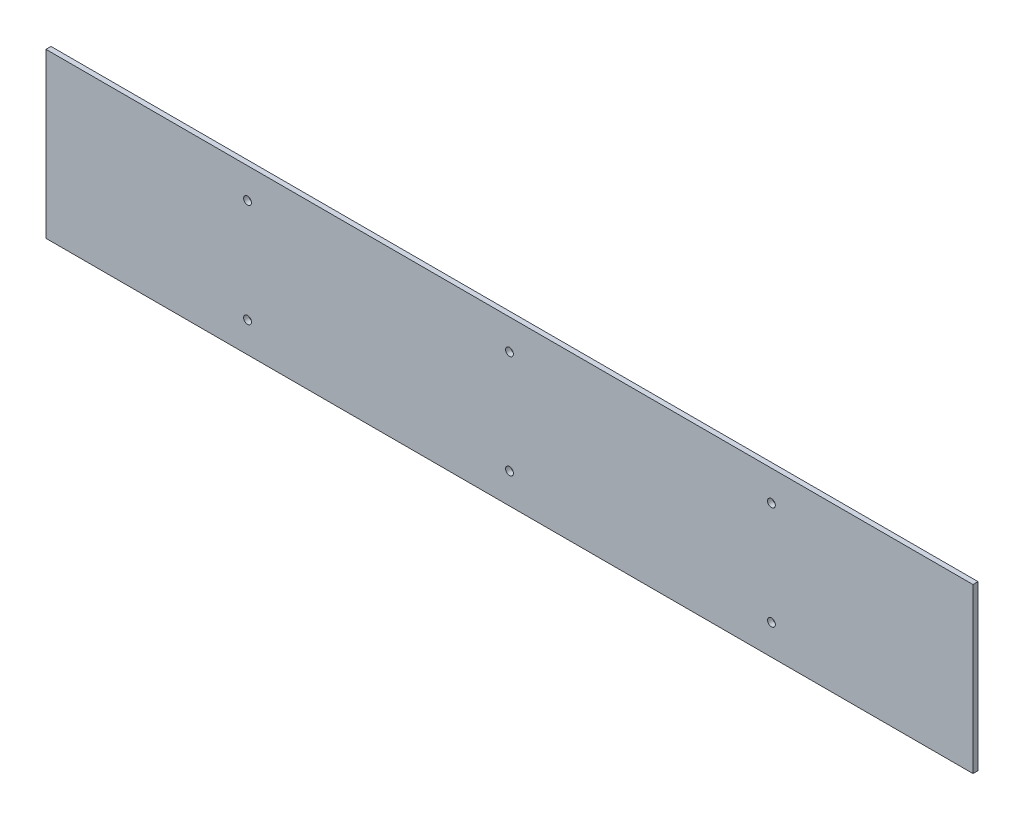
SolidWorks part; units mm, degrees
material "ABS PC"
ref_plane "Front Plane" through (0, 0, 0) normal (0, 0, 1) x (1, 0, 0)
ref_plane "Top Plane" through (0, 0, 0) normal (0, 1, 0) x (1, 0, 0)
ref_plane "Right Plane" through (0, 0, 0) normal (1, 0, 0) x (0, 0, -1)
sketch "Sketch2" plane through (0, 0, 0) normal (0, 0, 1) x (1, 0, 0)
  line L1 (0, 0) -> (584.2, 0)
  line L2 (0, 0) -> (0, 103.1875)
  line L3 (0, 103.1875) -> (584.2, 103.1875)
  line L4 (584.2, 0) -> (584.2, 103.1875)
  dimension "D1" = 103.1875
  dimension "D2" = 584.2
extrude "Boss-Extrude1" add sketch "Sketch2" along normal blind 3.175
hole_wizard "#10 (0.1935) Diameter Hole1" positions "Sketch3" profile "Sketch4" hole size "#10" standard "ANSI Inch" end condition through all
sketch "Sketch3" plane through (0, 0, 3.175) normal (0, 0, 1) x (1, 0, 0)
  line L2 (292.1, 103.1875) -> (292.1, 0) construction
  line L3 (584.2, 103.1875) -> (0, 103.1875) construction
  line L4 (0, 0) -> (584.2, 0) construction
  line L5 (127, 84.1375) -> (501.65, 84.1375) construction
  point P0 (127, 84.1375)
  point P2 (292.1, 84.1375)
  point P4 (457.2, 84.1375)
  dimension "D1" = 0
  dimension "D2" = 19.05
  dimension "D3" = 19.05
  dimension "D4" = 165.1
  dimension "D5" = 165.1
  dimension "D6" = 19.05
sketch "Sketch4" plane through (127, 84.1375, 3.175) normal (1, 0, 0) x (0, -1, 0)
  line L0 (0, 0) -> (0, 3.175)
  line L1 (0, 3.175) -> (2.4574, 3.175)
  line L2 (2.4574, 3.175) -> (2.4574, 0)
  line L5 (2.4574, 0) -> (0, 0)
  line L11 (0, -6.35) -> (0, 107.95) construction
  dimension "Thru Hole Dia." = 4.9149
  dimension "Thru Hole Depth" = 3.175
ref_plane "Plane4" through (0, 51.5938, 0) normal (0, 1, 0) x (1, 0, 0)
mirror "Mirror1" about plane through (0, 51.5938, 0) normal (0, 1, 0) of "#10 (0.1935) Diameter Hole1"
sketch "Sketch5" plane through (0, 0, 3.175) normal (0, 0, 1) x (1, 0, 0)
  line L1 (152.4, 67.4688) -> (203.2, 67.4688)
  line L2 (152.4, 67.4688) -> (152.4, 35.7188)
  line L3 (152.4, 35.7188) -> (203.2, 35.7188)
  line L4 (203.2, 67.4688) -> (203.2, 35.7188)
  line L5 (292.1, 67.4688) -> (342.9, 67.4688)
  line L6 (292.1, 67.4688) -> (292.1, 35.7188)
  line L7 (292.1, 35.7188) -> (342.9, 35.7188)
  line L8 (342.9, 67.4688) -> (342.9, 35.7188)
  line L9 (584.2, 0) -> (584.2, 103.1875) construction
  line L10 (292.1, 51.5938) -> (342.9, 51.5938) construction
  line L11 (0, 51.5938) -> (584.2, 51.5938) construction
  line L12 (0, 103.1875) -> (0, 0) construction
  line L13 (152.4, 51.5938) -> (203.2, 51.5938) construction
  dimension "D1" = 31.75
  dimension "D2" = 31.75
  dimension "D3" = 50.8
  dimension "D4" = 50.8
  dimension "D5" = 0
  dimension "D6" = 0
  dimension "D7" = 88.9
  dimension "D8" = 241.3
extrude "Cut-Extrude1" [suppressed] cut sketch "Sketch5" against normal blind 12.7
